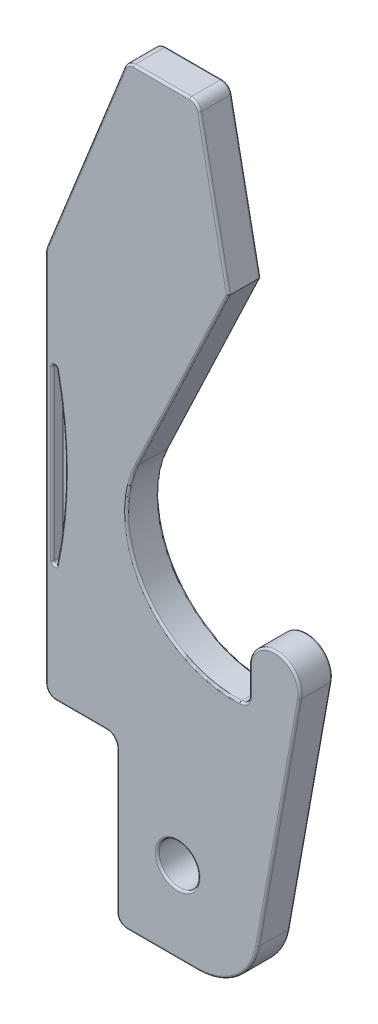
SolidWorks part; units mm, degrees
ref_plane "Płaszczyzna przednia" through (0, 0, 0) normal (0, 0, 1) x (1, 0, 0)
ref_plane "Płaszczyzna górna" through (0, 0, 0) normal (0, 1, 0) x (1, 0, 0)
ref_plane "Płaszczyzna prawa" through (0, 0, 0) normal (1, 0, 0) x (0, 0, -1)
sketch "Sketch1" plane through (0, 0, 0) normal (0, 0, 1) x (1, 0, 0)
  line L0 (0, 0) -> (0, 27)
  line L1 (0, 0) -> (12.5, 0) construction
  line L2 (0, 0) -> (0, 37) construction
  line L3 (0, 37) -> (12.5, 37) construction
  line L4 (12.5, 0) -> (12.5, 37) construction
  line L5 (0, 27) -> (4, 37)
  line L6 (4, 37) -> (7.5, 37)
  line L7 (7.5, 37) -> (9, 29.5)
  line L8 (9, 29.5) -> (4.4969, 20)
  line L11 (10, 0) -> (0, 0)
  line L12 (10, 0) -> (12.5, 14.0307)
  line L13 (10.0338, 14.4396) -> (10.0338, 12.5457)
  arc A2 (12.5, 14.0307) -> (10.0338, 14.4396) centre (11.2694, 14.25) ccw
  arc A3 (4.4969, 20) -> (10.0338, 12.5457) centre (9.25, 17.747) ccw
  dimension "D10" = 1.25
  dimension "D9" = 22.75
  dimension "D11" = 5.26
  dimension "D1" = 37
  dimension "D2" = 12.5
  dimension "D3" = 10
  dimension "D4" = 3.5
  dimension "D5" = 4
  dimension "D6" = 10
  dimension "D7" = 7.5
  dimension "D8" = 9.5
  dimension "D12" = 9.25
  dimension "D13" = 9
extrude "Boss-Extrude1" add sketch "Sketch1" along normal blind 1.6
fillet "Fillet1" radius 3 1 edges at (10, 0, 0.8)
sketch "Sketch2" plane through (0, 0, 1.6) normal (0, 0, 1) x (1, 0, 0)
  line L0 (0, 0) -> (7.4873, 0) construction
  line L1 (0, 0) -> (3.5, 0)
  line L2 (0, 0) -> (0, 8)
  line L3 (0, 8) -> (3.5, 8)
  line L4 (3.5, 0) -> (3.5, 8)
  circle A0 centre (6.5, 4) radius 1
  dimension "D3" = 2
  dimension "D1" = 8
  dimension "D2" = 3.5
  dimension "D4" = 4
  dimension "D5" = 3
extrude "Cut-Extrude1" cut sketch "Sketch2" against normal through all
fillet "Fillet2" radius 0.5 7 edges at (10.0338, 12.5457, 0.8) (7.5, 37, 0.8) (4, 37, 0.8) (0, 27, 0.8) (3.5, 0, 0.8) (3.5, 8, 0.8) (0, 8, 0.8)
fillet "Fillet3" radius 0.1 42 edges at (7.5, 4, 1.6) (6.7485, 24.75, 1.6) (4.8907, 14.8035, 1.6) (9.8978, 12.6526, 1.6) (10.0338, 13.7175, 1.6) (11.4738, 15.4832, 1.6) (11.4704, 8.2522, 1.6) (9.4136, 0.7001, 1.6) (5.7436, 0, 1.6) (3.6464, 0.1464, 1.6) (3.5, 4, 1.6) (3.3536, 7.8536, 1.6) (1.75, 8, 1.6) (0.1464, 8.1464, 1.6) (0, 17.7019, 1.6) (0.009, 26.9983, 1.6) (1.955, 31.8875, 1.6) (4.0582, 36.914, 1.6) (5.7143, 37, 1.6) (7.4071, 36.8867, 1.6) (8.2902, 33.049, 1.6) (4.0582, 36.914, 0) (1.955, 31.8875, 0) (0.009, 26.9983, 0) (0, 17.7019, 0) (0.1464, 8.1464, 0) (1.75, 8, 0) (3.3536, 7.8536, 0) (3.5, 4, 0) (3.6464, 0.1464, 0) (5.7436, 0, 0) (9.4136, 0.7001, 0) (11.4704, 8.2522, 0) (11.4738, 15.4832, 0) (10.0338, 13.7175, 0) (9.8978, 12.6526, 0) (4.8907, 14.8035, 0) (6.7485, 24.75, 0) (8.2902, 33.049, 0) (7.4071, 36.8867, 0) (5.7143, 37, 0) (7.5, 4, 0)
sketch "Sketch3" plane through (0, 0, 1.6) normal (0, 0, 1) x (1, 0, 0)
  line L0 (0.35, 23) -> (0.35, 13)
  line L1 (0.1, 26.9037) -> (0.1, 8.5) construction
  line L2 (3, 8) -> (0.5, 8) construction
  arc A0 (0.35, 23) -> (0.35, 13) centre (-19.0149, 18) cw
  dimension "D2" = 20
  dimension "D1" = 10
  dimension "D3" = 0.25
  dimension "D4" = 5
extrude "Cut-Extrude2" cut sketch "Sketch3" against normal blind 0.5
fillet "Fillet4" radius 0.1 2 edges at (0.35, 23, 1.35) (0.35, 13, 1.35)
fillet "Fillet5" radius 0.1 4 edges at (0.4395, 22.2379, 1.6) (0.35, 18, 1.6) (0.4395, 13.7621, 1.6) (0.9851, 18, 1.6)
